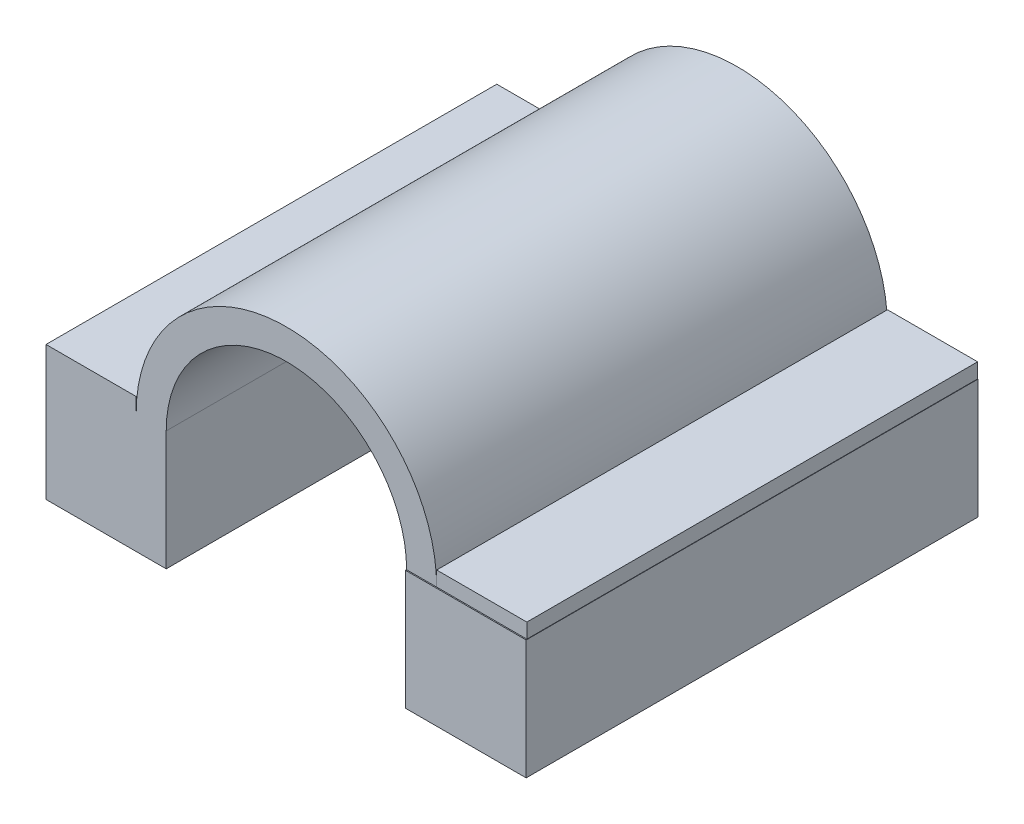
SolidWorks part; units mm, degrees
ref_plane "Front Plane" through (0, 0, 0) normal (0, 0, 1) x (1, 0, 0)
ref_plane "Top Plane" through (0, 0, 0) normal (0, 1, 0) x (1, 0, 0)
ref_plane "Right Plane" through (0, 0, 0) normal (1, 0, 0) x (0, 0, -1)
sketch "Sketch1" plane through (0, 0, 0) normal (0, 0, 1) x (1, 0, 0)
  line L0 (55, 0) -> (-55, 0) construction
  arc A1 (8, 0) -> (-8, 0) centre (0, 0) ccw
  dimension "D1" = 8
extrude "Extrude-Thin1" add sketch "Sketch1" along normal blind 30 thin
ref_plane "Plane1" through (-10, 0, 0) normal (-1, 0, 0) x (0, 0, 1)
sketch "Sketch2" plane through (-10, 0, 0) normal (-1, 0, 0) x (0, 0, 1)
  line L0 (30, 0) -> (30, 10) construction
  line L1 (0, 0) -> (30, 0)
  line L2 (0, 0) -> (0, 0.9848)
  line L3 (0, 0.9848) -> (30, 0.9848)
  line L4 (30, 0) -> (30, 0.9848)
extrude "Boss-Extrude1" add sketch "Sketch2" along normal blind 6 separate body
ref_plane "Plane2" through (10, 0, 0) normal (1, 0, 0) x (0, 0, -1)
sketch "Sketch3" plane through (10, 0, 0) normal (1, 0, 0) x (0, 0, -1)
  line L1 (0, 0) -> (-30, 0)
  line L2 (0, 0) -> (0, 0.9848)
  line L3 (0, 0.9848) -> (-30, 0.9848)
  line L4 (-30, 0) -> (-30, 0.9848)
extrude "Boss-Extrude2" add sketch "Sketch3" along normal blind 6 separate body
sketch "Sketch4" plane through (0, 0.9848, 0) normal (0, 1, 0) x (1, 0, 0)
  circle A0 centre (13.0921, -6.2713) radius 2
  circle A1 centre (13.0921, -23.8367) radius 2
  point P4 (22.9845, -6.2372)
  point P5 (22.9845, -23.8026)
  point P6 (0, 0)
  dimension "D1" = 4
sketch "Sketch5" plane through (0, 0.9848, 0) normal (0, 1, 0) x (1, 0, 0)
  circle A0 centre (-12.9709, -6.2555) radius 2
  circle A1 centre (-12.9709, -24.2204) radius 2
  point P2 (0, 0)
  point P3 (0, 0)
sketch "Sketch7" plane through (0, 0, 0) normal (0, 1, 0) x (1, 0, 0)
  line L0 (-5.5, 0) -> (5.5, 0) construction
  line L1 (16.0247, -30.0711) -> (8, -30.0711)
  line L2 (16.0247, -30.0711) -> (16.0247, 0)
  line L3 (16.0247, 0) -> (8, 0)
  line L4 (8, -30.0711) -> (8, 0)
  line L5 (8, -30) -> (8, 0) construction
  point P8 (8.0695, 0.0223)
extrude "Boss-Extrude3" add sketch "Sketch7" against normal blind 7.95
sketch "Sketch9" plane through (0, 0, 0) normal (0, -1, 0) x (1, 0, 0)
  line L1 (-16, 0) -> (-8, 0)
  line L2 (-16, 0) -> (-16, 30)
  line L3 (-16, 30) -> (-8, 30)
  line L4 (-8, 0) -> (-8, 30)
extrude "Boss-Extrude5" add sketch "Sketch9" along normal blind 7.95
